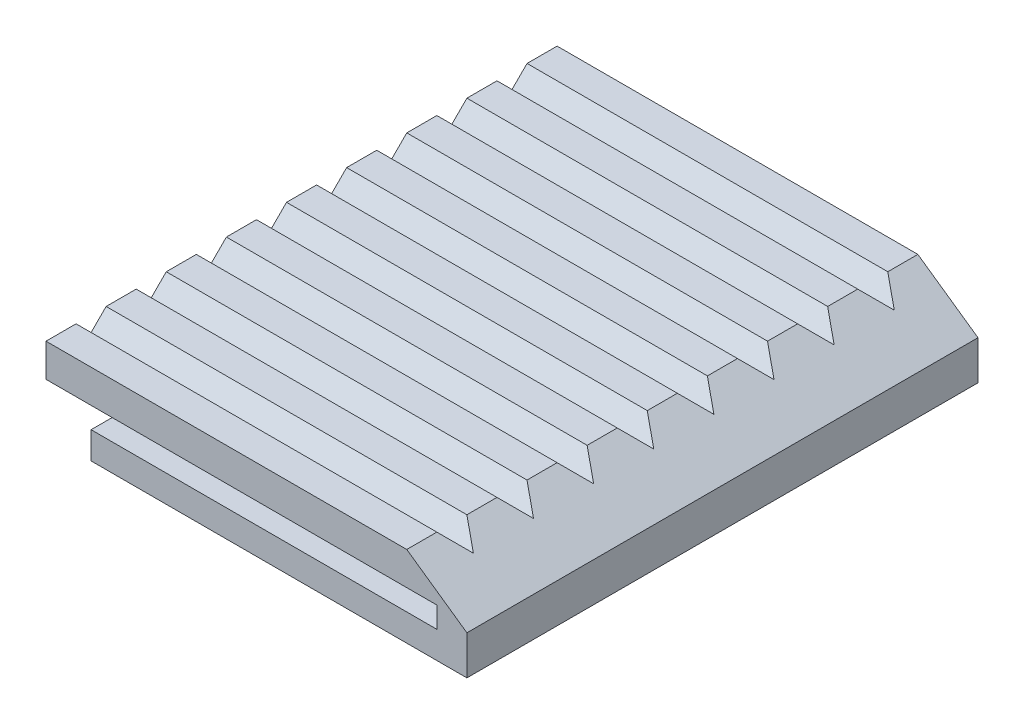
SolidWorks part; units mm, degrees
ref_plane "前视基准面" through (0, 0, 0) normal (0, 0, 1) x (1, 0, 0)
ref_plane "上视基准面" through (0, 0, 0) normal (0, 1, 0) x (1, 0, 0)
ref_plane "右视基准面" through (0, 0, 0) normal (1, 0, 0) x (0, 0, -1)
sketch "草图1" plane through (0, 0, 0) normal (0, 0, 1) x (1, 0, 0)
  line L0 (1.5, 0.0444) -> (14, 0.0444)
  line L1 (14, 0.0444) -> (14, 1.3444)
  line L2 (14, 1.3444) -> (12, 2.7444)
  line L3 (12, 2.7444) -> (0, 2.7444)
  line L4 (0, 2.7444) -> (0, 1.6444)
  line L5 (0, 1.6444) -> (1.5, 1.6444)
  line L6 (1.5, 1.6444) -> (1.5, 0.0444)
  point P0 (0, 0)
  dimension "D1" = 1.3
  dimension "D2" = 1.4
  dimension "D3" = 14
  dimension "D4" = 2
  dimension "D5" = 1.1
  dimension "D6" = 1.5
extrude "凸台-拉伸1" add sketch "草图1" along normal blind 17
sketch "草图4" plane through (0, 0.0444, 0) normal (0, -1, 0) x (1, 0, 0)
  line L0 (1.5, 15) -> (12, 15)
  line L1 (1.5, 17) -> (1.5, 0) construction
  line L2 (-1.2695, 8.5) -> (14.5323, 8.5) construction
  line L3 (12, 15) -> (12, 2)
  line L5 (1.5, 17) -> (1.5, 0) construction
  line L6 (1.5, 2) -> (1.5, 15)
  line L7 (1.5, 17) -> (14, 17) construction
  line L8 (14, 17) -> (14, 0) construction
  line L9 (1.5, 2) -> (12, 2)
  point P15 (1.5, 8.5)
  point P16 (12, 8.5)
  dimension "D1" = 2
  dimension "D2" = 2
extrude "切除-拉伸1" cut sketch "草图4" against normal up to surface (1.6 mm away) up to face at (0.75, 1.6444, 8.5)
sketch "草图5" plane through (0, 0, 0) normal (-1, 0, 0) x (0, 0, 1)
  line L0 (8.5, 3.841) -> (8.5, -1.5105) construction
  line L1 (0, 1.6444) -> (0, 0.9444)
  line L2 (0, 2.7444) -> (1, 2.7444)
  line L3 (0, 0.9444) -> (0.7, 0.9444)
  line L4 (0.7, 0.9444) -> (0.7, 1.6444)
  line L5 (2, 1.6444) -> (0, 1.6444) construction
  line L6 (0.7, 1.6444) -> (0, 1.6444)
  line L7 (17, 2.7444) -> (0, 2.7444) construction
  line L8 (1, 2.7444) -> (1.5, 2.2444)
  line L9 (1.5, 2.2444) -> (2, 2.7444)
  line L10 (0, 2.7444) -> (0, 3.7444)
  line L11 (2, 2.7444) -> (3, 2.7444)
  line L12 (3, 2.7444) -> (3.5, 2.2444)
  line L13 (3.5, 2.2444) -> (4, 2.7444)
  line L14 (4, 2.7444) -> (5, 2.7444)
  line L15 (5, 2.7444) -> (5.5, 2.2444)
  line L16 (5.5, 2.2444) -> (6, 2.7444)
  line L17 (6, 2.7444) -> (7, 2.7444)
  line L18 (7, 2.7444) -> (7.5, 2.2444)
  line L19 (7.5, 2.2444) -> (8, 2.7444)
  line L20 (8, 2.7444) -> (9, 2.7444)
  line L21 (9, 2.7444) -> (9.5, 2.2444)
  line L22 (9.5, 2.2444) -> (10, 2.7444)
  line L23 (10, 2.7444) -> (11, 2.7444)
  line L24 (11, 2.7444) -> (11.5, 2.2444)
  line L25 (11.5, 2.2444) -> (12, 2.7444)
  line L26 (12, 2.7444) -> (13, 2.7444)
  line L27 (13, 2.7444) -> (13.5, 2.2444)
  line L28 (13.5, 2.2444) -> (14, 2.7444)
  line L29 (14, 2.7444) -> (15, 2.7444)
  line L30 (15, 2.7444) -> (15.5, 2.2444)
  line L31 (15.5, 2.2444) -> (16, 2.7444)
  line L32 (16, 2.7444) -> (17, 2.7444)
  line L33 (16.3, 1.6444) -> (17, 1.6444)
  line L34 (16.3, 0.9444) -> (16.3, 1.6444)
  line L35 (0, 3.7444) -> (17, 3.7444)
  line L36 (17, 3.7444) -> (17, 2.7444)
  line L37 (17, 0.9444) -> (16.3, 0.9444)
  line L38 (17, 2.7444) -> (17.5, 2.2444) [skipped]
  line L39 (17.5, 2.2444) -> (18, 2.7444) [skipped]
  line L40 (17, 1.6444) -> (17, 0.9444)
  point P14 (4.5, 2.7444)
  dimension "D1" = 0.7
  dimension "D2" = 0.7
  dimension "D3" = 1
  dimension "D4" = 1
  dimension "D5" = 90
  dimension "D6" = 135
  dimension "D8" = 1
  dimension "D7" = 9
extrude "切除-拉伸2" cut sketch "草图5" against normal blind 13
